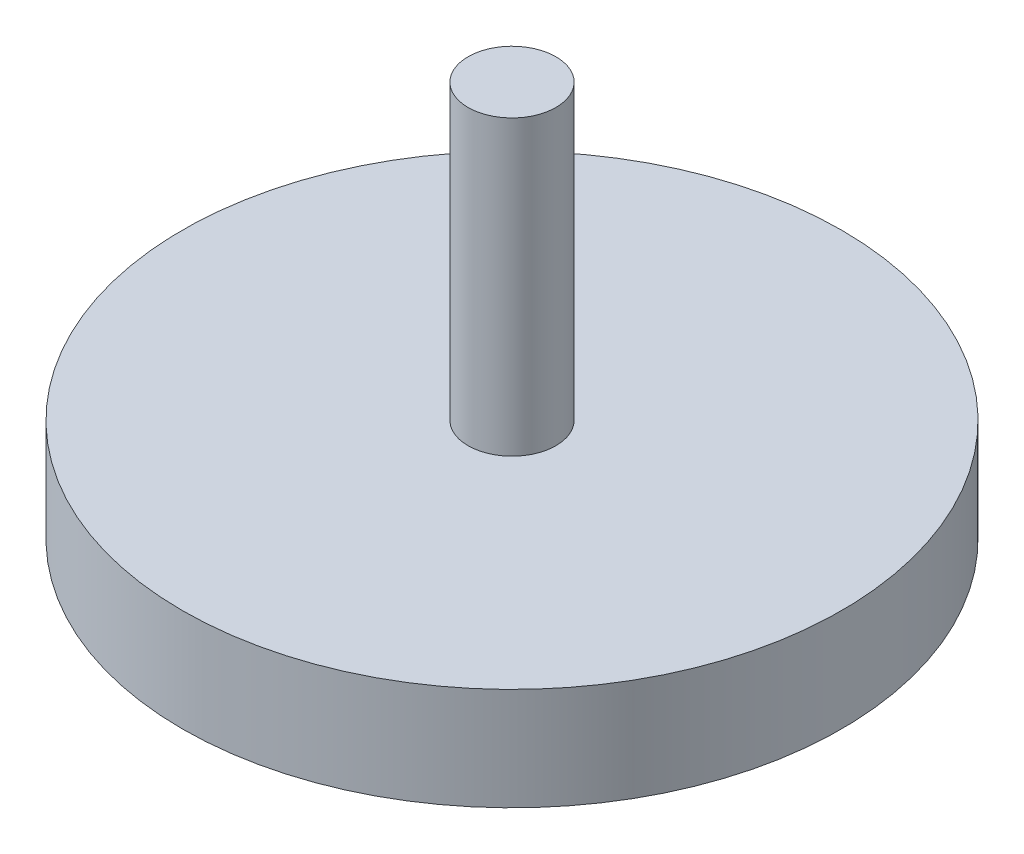
SolidWorks part; units mm, degrees
ref_plane "Front Plane" through (0, 0, 0) normal (0, 0, 1) x (1, 0, 0)
ref_plane "Top Plane" through (0, 0, 0) normal (0, 1, 0) x (1, 0, 0)
ref_plane "Right Plane" through (0, 0, 0) normal (1, 0, 0) x (0, 0, -1)
sketch "Sketch1" plane through (0, 0, 0) normal (0, 1, 0) x (1, 0, 0)
  circle A0 centre (0, 0) radius 22.5
  dimension "D1" = 45
extrude "Boss-Extrude1" add sketch "Sketch1" along normal blind 7
sketch "Sketch2" plane through (0, 7, 0) normal (0, 1, 0) x (1, 0, 0)
  circle A0 centre (0, 0) radius 3
  dimension "D1" = 6
extrude "Boss-Extrude2" add sketch "Sketch2" along normal blind 20
sketch "Sketch3" plane through (0, 0, 0) normal (0, -1, 0) x (1, 0, 0)
  line L0 (22.5, 0) -> (22.5, 19.5558) construction
  line L1 (4.7631, -2.75) -> (4.7631, 2.75)
  line L2 (4.7631, 2.75) -> (0, 5.5)
  line L3 (0, 5.5) -> (-4.7631, 2.75)
  line L4 (-4.7631, 2.75) -> (-4.7631, -2.75)
  line L5 (-4.7631, -2.75) -> (0, -5.5)
  line L6 (0, -5.5) -> (4.7631, -2.75)
  circle A0 centre (0, 0) radius 4.7631 construction
  circle A2 centre (0, 0) radius 22.5 construction
  dimension "D2" = 0
  dimension "D1" = 5.5
extrude "Cut-Extrude1" cut sketch "Sketch3" against normal blind 5
